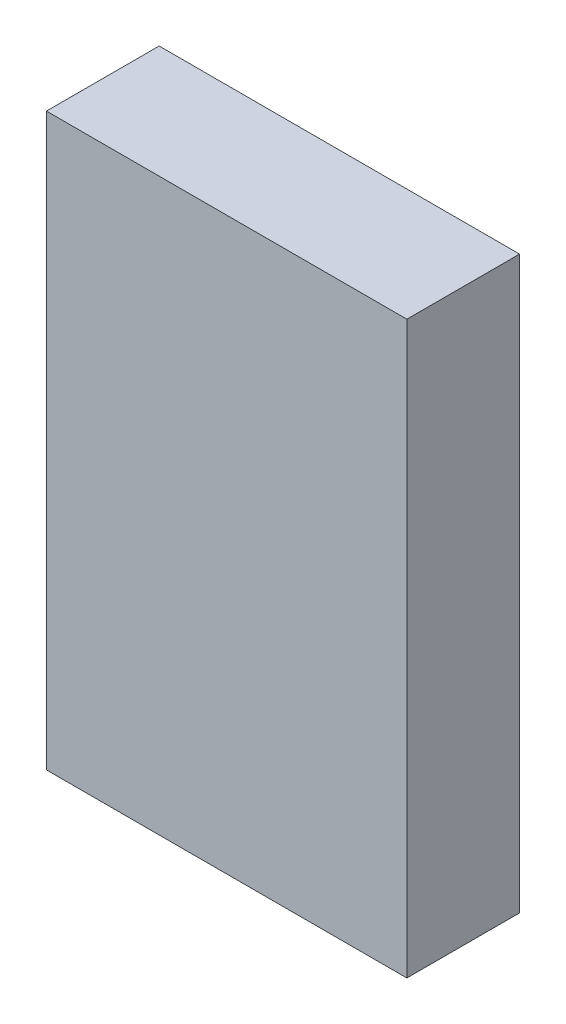
SolidWorks part; units mm, degrees
ref_plane "Front Plane" through (0, 0, 0) normal (0, 0, 1) x (1, 0, 0)
ref_plane "Top Plane" through (0, 0, 0) normal (0, 1, 0) x (1, 0, 0)
ref_plane "Right Plane" through (0, 0, 0) normal (1, 0, 0) x (0, 0, -1)
sketch "Sketch1" plane through (0, 0, 0) normal (0, 0, 1) x (1, 0, 0)
  line L1 (52.3875, -82.931) -> (-52.3875, -82.931)
  line L2 (52.3875, -82.931) -> (52.3875, 82.931)
  line L3 (52.3875, 82.931) -> (-52.3875, 82.931)
  line L4 (-52.3875, -82.931) -> (-52.3875, 82.931)
  line L5 (52.3875, -82.931) -> (-52.3875, 82.931) construction
  line L6 (52.3875, 82.931) -> (-52.3875, -82.931) construction
  point P0 (0, 0)
extrude "Boss-Extrude1" add sketch "Sketch1" against normal blind 32.766
sketch "Sketch2" plane through (0, 0, -32.766) normal (0, 0, -1) x (-1, 0, 0)
  line L1 (50.8, -60.325) -> (-50.8, -60.325)
  line L2 (50.8, -60.325) -> (50.8, 60.325)
  line L3 (50.8, 60.325) -> (-50.8, 60.325)
  line L4 (-50.8, -60.325) -> (-50.8, 60.325)
  line L5 (50.8, -60.325) -> (-50.8, 60.325) construction
  line L6 (50.8, 60.325) -> (-50.8, -60.325) construction
  point P0 (0, 0)
extrude "Cut-Extrude1" cut sketch "Sketch2" against normal blind 25.4
